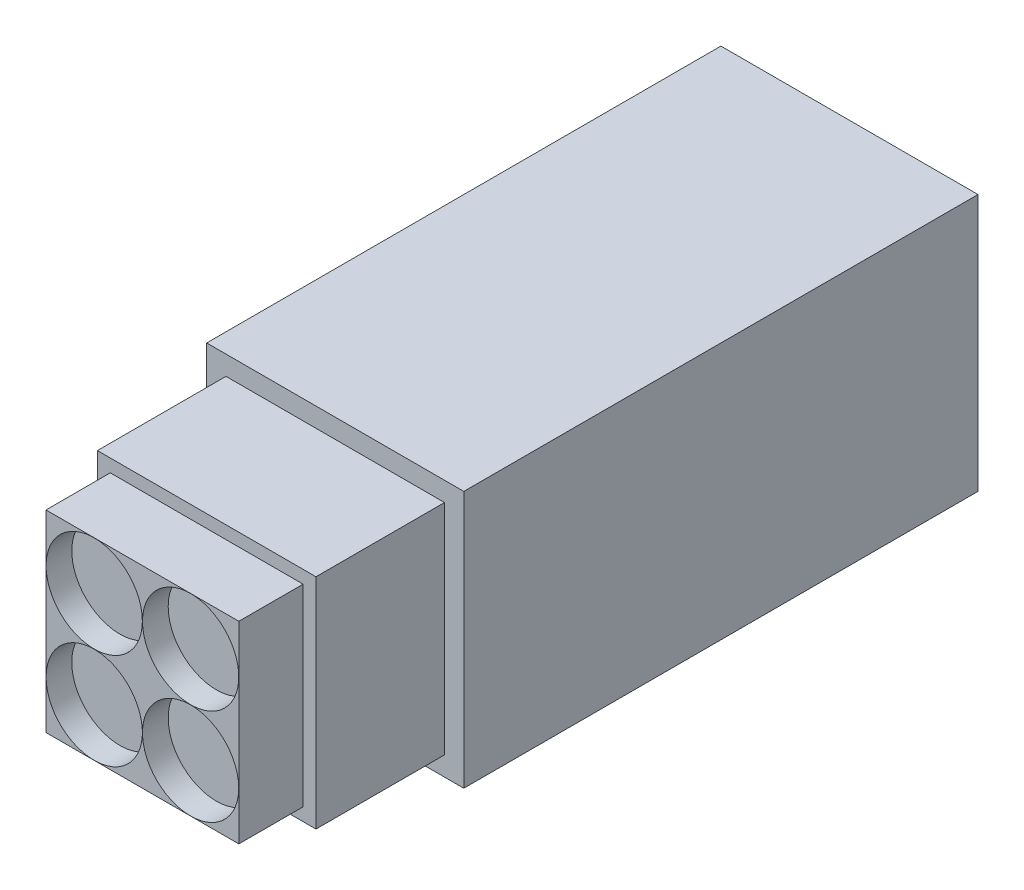
SolidWorks part; units mm, degrees
ref_plane "正面" through (0, 0, 0) normal (0, 0, 1) x (1, 0, 0)
ref_plane "平面" through (0, 0, 0) normal (0, 1, 0) x (1, 0, 0)
ref_plane "右側面" through (0, 0, 0) normal (1, 0, 0) x (0, 0, -1)
sketch "ｽｹｯﾁ1" plane through (0, 0, 0) normal (0, 0, 1) x (1, 0, 0)
  line L1 (-10, 10) -> (10, 10)
  line L2 (-10, 10) -> (-10, -10)
  line L3 (-10, -10) -> (10, -10)
  line L4 (10, 10) -> (10, -10)
  line L5 (-10, 10) -> (10, -10) construction
  line L6 (-10, -10) -> (10, 10) construction
  point P0 (0, 0)
  dimension "D1" = 20
extrude "ﾎﾞｽ - 押し出し1" add sketch "ｽｹｯﾁ1" along normal blind 40
sketch "ｽｹｯﾁ2" plane through (0, 0, 40) normal (0, 0, 1) x (1, 0, 0)
  line L0 (10, 10) -> (-10, -10) construction
  line L1 (-10, 10) -> (10, -10) construction
  line L3 (-8.5, 8.5) -> (8.5, 8.5)
  line L4 (-8.5, 8.5) -> (-8.5, -8.5)
  line L5 (-8.5, -8.5) -> (8.5, -8.5)
  line L6 (8.5, 8.5) -> (8.5, -8.5)
  line L7 (-8.5, 8.5) -> (8.5, -8.5) construction
  line L8 (-8.5, -8.5) -> (8.5, 8.5) construction
  point P8 (0, 0)
  dimension "D1" = 17
extrude "ﾎﾞｽ - 押し出し2" add sketch "ｽｹｯﾁ2" along normal blind 10
sketch "ｽｹｯﾁ3" plane through (0, 0, 50) normal (0, 0, 1) x (1, 0, 0)
  line L0 (8.5, 8.5) -> (-8.5, -8.5) construction
  line L1 (-8.5, 8.5) -> (8.5, -8.5) construction
  line L3 (-7.5, 7.5) -> (7.5, 7.5)
  line L4 (-7.5, 7.5) -> (-7.5, -7.5)
  line L5 (-7.5, -7.5) -> (7.5, -7.5)
  line L6 (7.5, 7.5) -> (7.5, -7.5)
  line L7 (-7.5, 7.5) -> (7.5, -7.5) construction
  line L8 (-7.5, -7.5) -> (7.5, 7.5) construction
  point P8 (0, 0)
  dimension "D1" = 15
extrude "ﾎﾞｽ - 押し出し3" add sketch "ｽｹｯﾁ3" along normal blind 5
sketch "ｽｹｯﾁ4" plane through (0, 0, 55) normal (0, 0, 1) x (1, 0, 0)
  line L0 (0, 7.5) -> (0, -7.5) construction
  line L1 (7.5, 7.5) -> (-7.5, 7.5) construction
  line L2 (-7.5, -7.5) -> (7.5, -7.5) construction
  line L3 (-7.5, 0) -> (7.5, 0) construction
  line L4 (-7.5, 7.5) -> (-7.5, -7.5) construction
  line L5 (7.5, -7.5) -> (7.5, 7.5) construction
  line L6 (-7.5, 7.5) -> (7.5, -7.5) construction
  line L7 (7.5, 7.5) -> (-7.5, -7.5) construction
  line L8 (0, 7.5) -> (7.5, 0) construction
  line L9 (-7.5, 0) -> (0, -7.5) construction
  line L10 (0, -7.5) -> (7.5, 0) construction
  line L11 (-7.5, 0) -> (0, 7.5) construction
  circle A0 centre (-3.75, 3.75) radius 3.745
  circle A1 centre (3.75, 3.75) radius 3.745
  circle A2 centre (3.75, -3.75) radius 3.745
  circle A3 centre (-3.75, -3.75) radius 3.745
  dimension "D1" = 7.49
extrude "ｶｯﾄ - 押し出し1" cut sketch "ｽｹｯﾁ4" against normal blind 2
